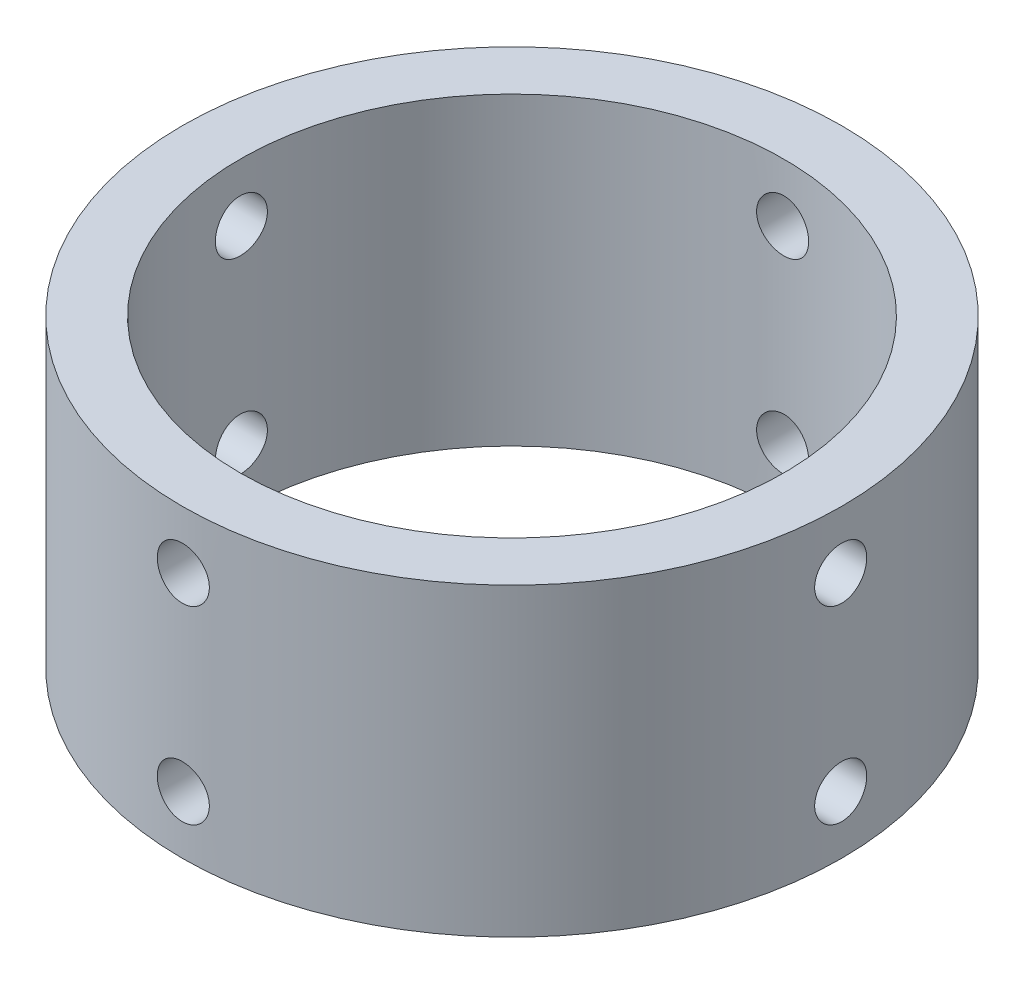
SolidWorks part; units mm, degrees
ref_plane "Front Plane" through (0, 0, 0) normal (0, 0, 1) x (1, 0, 0)
ref_plane "Top Plane" through (0, 0, 0) normal (0, 1, 0) x (1, 0, 0)
ref_plane "Right Plane" through (0, 0, 0) normal (1, 0, 0) x (0, 0, -1)
sketch "Sketch1" plane through (0, 0, 0) normal (0, 1, 0) x (1, 0, 0)
  circle A0 centre (0, 0) radius 28.5
  circle A1 centre (0, 0) radius 23.5
  dimension "D1" = 57
  dimension "D2" = 47
extrude "Boss-Extrude1" add sketch "Sketch1" along normal mid plane 26.35
sketch "Sketch2" plane through (0, 0, 0) normal (0, 0, 1) x (1, 0, 0)
  line L0 (-28.5, 0) -> (28.5, 0) construction
  line L1 (-28.5, 13.175) -> (-28.5, -13.175) construction
  line L2 (28.5, -13.175) -> (28.5, 13.175) construction
  circle A0 centre (0, 8.175) radius 2.25
  circle A1 centre (0, -8.175) radius 2.25
  point P3 (0, 6.5143)
  point P10 (3.1869, 8.175)
  point P11 (0, 0)
  dimension "D1" = 4.5
  dimension "D2" = 16.35
extrude "Cut-Extrude1" cut sketch "Sketch2" against normal through all
pattern_circular "CirPattern1" count 4 every 90 about axis through (0, 13.175, 0) along (0, -1, 0) of "Cut-Extrude1"
